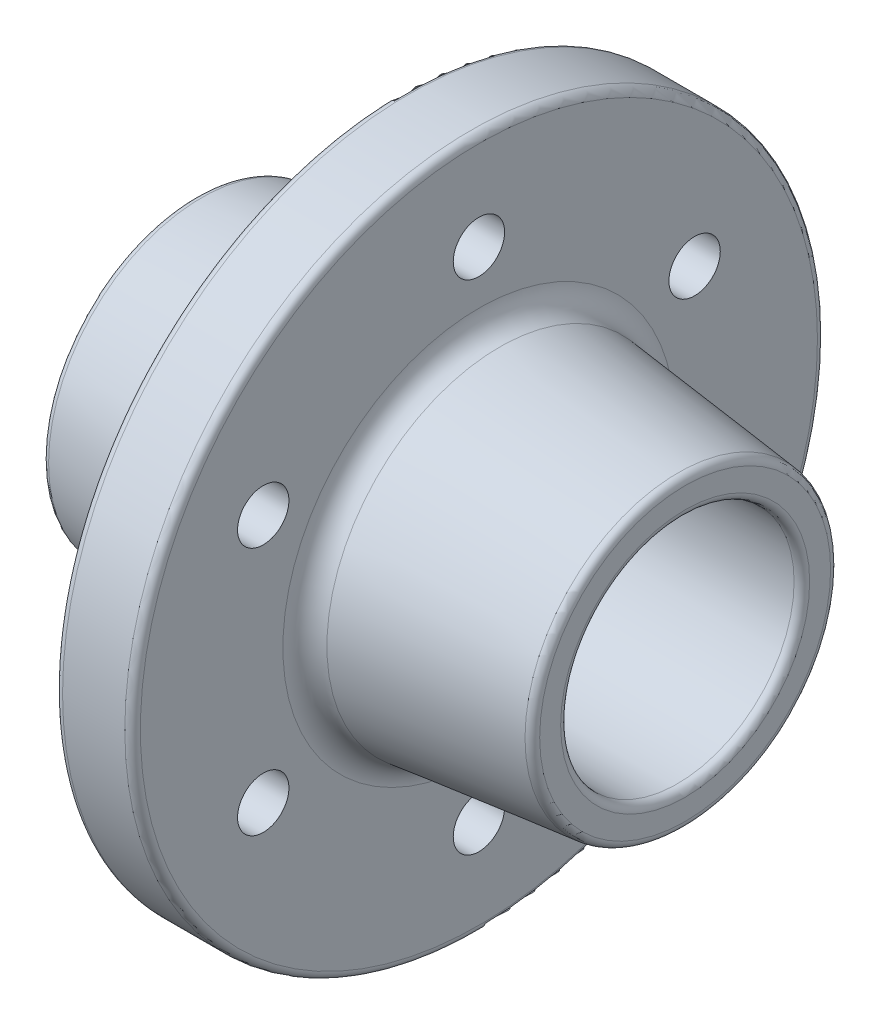
SolidWorks part; units mm, degrees
ref_plane "Front Plane" through (0, 0, 0) normal (0, 0, 1) x (1, 0, 0)
ref_plane "Top Plane" through (0, 0, 0) normal (0, 1, 0) x (1, 0, 0)
ref_plane "Right Plane" through (0, 0, 0) normal (1, 0, 0) x (0, 0, -1)
sketch "Sketch1" plane through (0, 0, 0) normal (1, 0, 0) x (0, 0, -1)
  circle A0 centre (0, 0) radius 44.5
  dimension "D1" = 89
extrude "Boss-Extrude1" add sketch "Sketch1" along normal blind 10
sketch "Sketch3" plane through (0, 0, 0) normal (-1, 0, 0) x (0, 0, 1)
  circle A0 centre (0, 0) radius 22.5
  dimension "D1" = 45
extrude "Boss-Extrude2" add sketch "Sketch3" along normal blind 26.5 draft 6.27
sketch "Sketch4" plane through (10, 0, 0) normal (1, 0, 0) x (0, 0, -1)
  circle A0 centre (0, 0) radius 22.5
  dimension "D1" = 45
extrude "Boss-Extrude3" add sketch "Sketch4" along normal blind 26.5 draft 6.27
fillet "Fillet1" radius 3 1 edges at (10, 0, -22.5)
fillet "Fillet2" radius 3 1 edges at (0, 0, 22.5)
sketch "Sketch5" plane through (36.5, 0, 0) normal (1, 0, 0) x (0, 0, -1)
  circle A0 centre (0, 0) radius 15
  dimension "D1" = 30
extrude "Cut-Extrude1" cut sketch "Sketch5" against normal through all
fillet "Fillet3" radius 1 2 edges at (36.5, 0, -15) (36.5, 0, -19.5884)
fillet "Fillet4" radius 1 2 edges at (-26.5, 0, -15) (-26.5, 0, 19.5884)
fillet "Fillet5" radius 1 2 edges at (0, 0, -44.5) (10, 0, -44.5)
sketch "Sketch8" plane through (10, 0, 0) normal (1, 0, 0) x (0, 0, -1)
  circle A0 centre (0, 0) radius 32 construction
  dimension "D1" = 64
hole_wizard "M6 Clearance Hole2" positions "Sketch11" profile "Sketch12" hole size "M6" standard "ISO" end condition through all
sketch "Sketch11" plane through (0, 0, 0) normal (-1, 0, 0) x (0, 0, 1)
  circle A0 centre (0, 0) radius 32 construction
  point P0 (0, 32)
sketch "Sketch12" plane through (0, 32, 0) normal (0, 1, 0) x (0, 0, 1)
  line L0 (0, 0) -> (0, 36.5)
  line L1 (0, 36.5) -> (3.3, 36.5)
  line L2 (3.3, 36.5) -> (3.3, 0)
  line L5 (3.3, 0) -> (0, 0)
  line L11 (0, -6.35) -> (0, 107.95) construction
  dimension "Thru Hole Dia." = 6.6
  dimension "Thru Hole Depth" = 36.5
pattern_circular "CirPattern2" count 6 over 360 about axis through (0, 0, 0) along (1, 0, 0) of "M6 Clearance Hole2"
